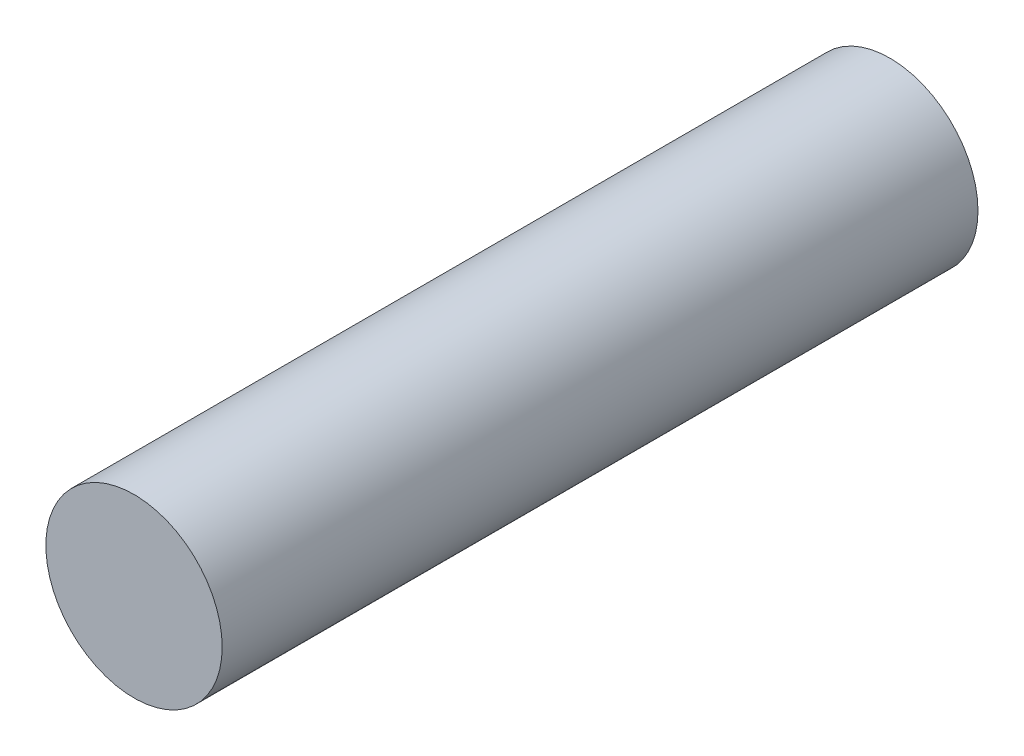
SolidWorks part; units mm, degrees
ref_plane "Front" through (0, 0, 0) normal (0, 0, 1) x (1, 0, 0)
ref_plane "Top" through (0, 0, 0) normal (0, 1, 0) x (1, 0, 0)
ref_plane "Right" through (0, 0, 0) normal (1, 0, 0) x (0, 0, -1)
sketch "Sketch1" plane through (0, 0, 0) normal (0, 0, 1) x (1, 0, 0)
  circle A0 centre (0, 0) radius 1.75
  dimension "D1" = 3.5
extrude "Boss-Extrude1" add sketch "Sketch1" along normal blind 15
